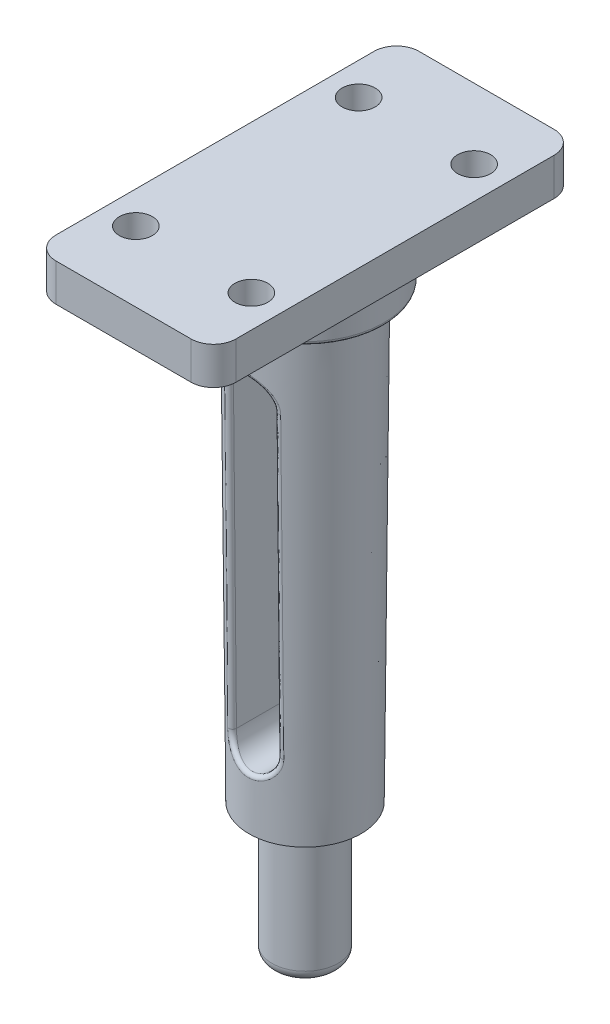
SolidWorks part; units mm, degrees
ref_plane "Front Plane" through (0, 0, 0) normal (0, 0, 1) x (1, 0, 0)
ref_plane "Top Plane" through (0, 0, 0) normal (0, 1, 0) x (1, 0, 0)
ref_plane "Right Plane" through (0, 0, 0) normal (1, 0, 0) x (0, 0, -1)
sketch "Sketch1" plane through (0, 0, 0) normal (0, 1, 0) x (1, 0, 0)
  line L1 (-12, -24.2) -> (12, -24.2)
  line L2 (-12, -24.2) -> (-12, 24.2)
  line L3 (-12, 24.2) -> (12, 24.2)
  line L4 (12, -24.2) -> (12, 24.2)
  line L5 (-12, -24.2) -> (12, 24.2) construction
  line L6 (-12, 24.2) -> (12, -24.2) construction
  point P0 (0, 0)
  dimension "D1" = 48.4
  dimension "D2" = 24
extrude "Boss-Extrude1" add sketch "Sketch1" along normal blind 5
sketch "Sketch3" plane through (0, 0, 0) normal (0, -1, 0) x (1, 0, 0)
  line L0 (-12, 0) -> (12, 0) construction
  line L1 (-12, -24.2) -> (-12, 24.2) construction
  line L2 (12, 24.2) -> (12, -24.2) construction
  circle A0 centre (0, 0) radius 10.5
  dimension "D1" = 21
extrude "Boss-Extrude3" add sketch "Sketch3" along normal blind 5
sketch "Sketch4" plane through (0, -5, 0) normal (0, -1, 0) x (1, 0, 0)
  circle A0 centre (0, 0) radius 8
  point P0 (0, 0)
  point P6 (0, 0)
  dimension "D1" = 16
extrude "Boss-Extrude4" add sketch "Sketch4" along normal blind 60 draft 0.5
sketch "Sketch5" plane through (0, 5, 0) normal (0, 1, 0) x (1, 0, 0)
  line L0 (-12, 24.2) -> (-12, -24.2) construction
  line L1 (-12, 0) -> (12, 0) construction
  line L2 (12, -24.2) -> (12, 24.2) construction
  line L3 (0, 24.2) -> (0, -24.2) construction
  line L4 (12, 24.2) -> (-12, 24.2) construction
  line L5 (-12, -24.2) -> (12, -24.2) construction
  circle A4 centre (-7.7, 14.85) radius 2.2
  circle A5 centre (7.7, 14.85) radius 2.2
  circle A6 centre (7.7, -14.85) radius 2.2
  circle A7 centre (-7.7, -14.85) radius 2.2
  dimension "D1" = 14.85
  dimension "D2" = 15.4
  dimension "D3" = 4.4
extrude "Cut-Extrude1" cut sketch "Sketch5" against normal blind 5
sketch "Sketch6" plane through (0, -65, 0) normal (0, -1, 0) x (1, 0, 0)
  circle A0 centre (0, 0) radius 4.4
  dimension "D1" = 8.8
extrude "Boss-Extrude5" add sketch "Sketch6" along normal blind 18
sketch "Sketch8" plane through (0, 0, 0) normal (0, 0, 1) x (1, 0, 0)
  line L0 (0, -5) -> (0, -83) construction
  line L1 (-8, -5) -> (8, -5) construction
  line L2 (-4.4, -83) -> (4.4, -83) construction
  line L3 (-7.7382, -35) -> (7.7382, -35) construction
  line L4 (-8, -5) -> (-7.4764, -65) construction
  line L5 (7.4764, -65) -> (8, -5) construction
  line L8 (3, -55) -> (3, -15)
  line L10 (-3, -55) -> (-3, -15)
  arc A0 (3, -15) -> (-3, -15) centre (0, -15) ccw
  arc A1 (-3, -55) -> (3, -55) centre (0, -55) ccw
  point P12 (0, -35)
  point P24 (3, -35)
  dimension "D1" = 40
  dimension "D2" = 6
extrude "Cut-Extrude2" cut sketch "Sketch8" against normal mid plane 200
fillet "Fillet2" radius 3 4 edges at (-12, 2.5, 24.2) (12, 2.5, 24.2) (-12, 2.5, -24.2) (12, 2.5, -24.2)
fillet "Fillet3" radius 1.5 1 edges at (0, -83, -4.4)
fillet "Fillet4" radius 0.5 12 edges at (0, -65, -4.4) (0, 0, -10.5) (0, -5, -10.5) (0, -5, -8) (0.2313, -57.9911, -7.534) (-0.2313, -57.9911, 7.534) (-0.2532, -12.0107, -7.9348) (0.2532, -12.0107, 7.9348)
